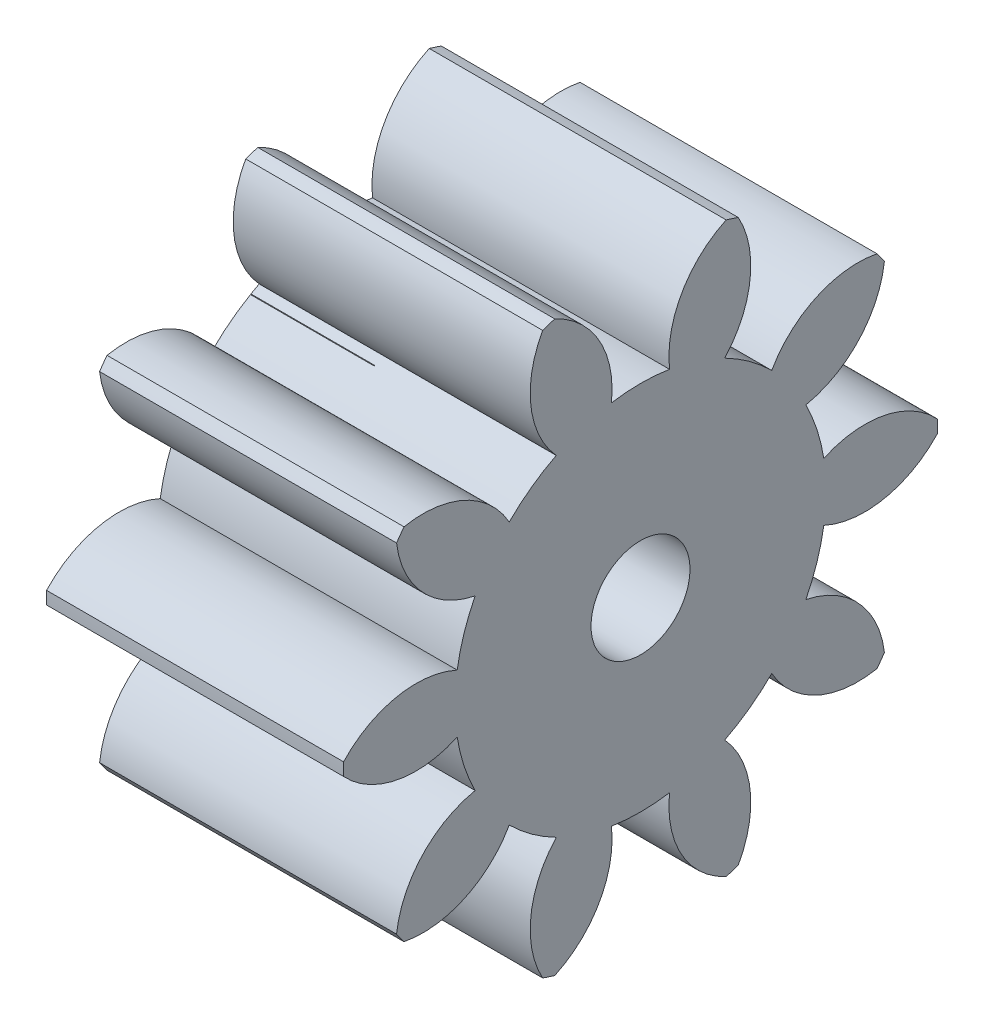
SolidWorks part; units mm, degrees
ref_plane "Plane1" through (0, 0, 0) normal (0, 0, 1) x (1, 0, 0)
ref_plane "Plane2" through (0, 0, 0) normal (0, 1, 0) x (1, 0, 0)
ref_plane "Plane3" through (0, 0, 0) normal (1, 0, 0) x (0, 0, -1)
sketch "HoldingSke" plane through (0, 0, 0) normal (0, 1, 0) x (1, 0, 0)
  line L0 (0, 0) -> (0.4924, -0.0868)
  line L1 (-15, 0) -> (100, 0) construction
  line L2 (0, 0) -> (-2.1039, 2.3779)
  line L3 (0, 0) -> (-11.863, 4.5341)
  line L4 (0, 0) -> (8.5048, 1.4996)
  line L5 (0, 0) -> (-46.8476, -17.4728)
  line L6 (0, 0) -> (-9.9476, -6.7116)
  line L7 (-2.1039, 2.3779) -> (8.6586, 51.2059)
  line L8 (-76.2, 54.61) -> (-75.5, 54.61)
  line L9 (-71.009, 38.7566) -> (-53.1078, 45.2721)
  line L10 (-76.2, 71.12) -> (104.1128, 71.12)
  line L11 (0, 0) -> (-12, 0)
  line L12 (-76.2, 101.6) -> (-76.133, 101.6)
  line L13 (24.9733, 27.94) -> (52.9518, 28.4284)
  line L14 (24.9733, 27.94) -> (24.9743, 27.94)
  line L15 (24.9733, 27.94) -> (100.4006, 29.5858)
  line L16 (-63.627, -2) -> (-12.827, -2)
  circle A0 centre (0, 0) radius 2
  circle A1 centre (0, 0) radius 7.499
  circle A2 centre (0, 0) radius 37.5
  circle A3 centre (0, 0) radius 2
  dimension "MHD" = 14.998
  dimension "Hub_dia" = 75
  dimension "Bore" = 4
  dimension "MBD" = 4
  dimension "Num_teeth" = 10
  dimension "Pitch_radius" = 180.3128
  dimension "Pitch" = 0.5
  dimension "Width" = 12
  dimension "Overall_len" = 50
  dimension "Show_teeth" = 10
  dimension "Thickness" = 12
  dimension "OAL" = 50.0001
  dimension "T_dim" = 0.7
  dimension "Ap" = 20
  dimension "H" = 19.05
  dimension "Backlash" = 0.067
  dimension "Addendum_fac" = 1
  dimension "Dedendum_fac" = 1.25
  dimension "Clearance_fac" = 0.25
  dimension "Dedendum_add" = 0.001
  dimension "Module" = 2
sketch "BasProSke" plane through (0, 0, 0) normal (0, 1, 0) x (1, 0, 0)
  line L0 (-10, 0) -> (60, 0) construction
  line L1 (0, 0) -> (0, 12)
  line L2 (0, 0) -> (12, 0)
  line L3 (12, 0) -> (12, 12)
  line L4 (12, 12) -> (0, 12)
  dimension "Diameter" = 24
  dimension "Thickness" = 12
revolve "Base-Revolve" add sketch "BasProSke" angle 360 about L0
sketch "TooCutSke" plane through (0, 0, 0) normal (1, 0, 0) x (0, 0, -1)
  line L1 (0, 0) -> (0, 107) construction
  line L2 (0, 0) -> (-1.6814, 9.8576) construction
  line L3 (0, 0) -> (-6.1153, 18.8209) construction
  line L4 (-1.6814, 9.8576) -> (-3.0576, 9.4105) construction
  arc A0 (1.1737, 7.4066) -> (-1.1737, 7.4066) centre (0, 0) ccw
  arc A1 (3.4979, 11.5054) -> (-3.4979, 11.5054) centre (0, 0) ccw
  circle A2 centre (0, 0) radius 10 construction
  circle A3 centre (0, 0) radius 9.3969 construction
  arc A4 (-1.1737, 7.4066) -> (-3.4979, 11.5054) centre (-5.1477, 7.8615) ccw
  arc A5 (3.4979, 11.5054) -> (1.1737, 7.4066) centre (5.1477, 7.8615) ccw
  dimension "Root_dia" = 14.998
  dimension "Overcut_dia" = 24.0508
  dimension "Pitch_dia" = 20
  dimension "Base_dia" = 18.7939
  dimension "Flank_rad" = 4
  dimension "Half_ang" = 18
  dimension "Half_CT" = 1.4471
extrude "ToothCut" cut sketch "TooCutSke" along normal through all
fillet "Breaks" [suppressed] radius 0.04
fillet "RootFillets" [suppressed] radius 0.501
pattern_circular "TeethCuts" count 10 every 36 about axis through (-10, 0, 0) along (1, 0, 0) of "ToothCut", "RootFillets", "Breaks"
sketch "HubNeaOneSke" [suppressed] plane through (0, 0, 0) normal (-1, 0, 0) x (0, 0, 1)
  circle A0 centre (0, 0) radius 12.7
  dimension "Diameter" = 14.998
extrude "HubNearOne" [suppressed] add sketch "HubNeaOneSke" along normal blind 38.0001
sketch "HubNeaBotSke" [suppressed] plane through (0, 0, 0) normal (-1, 0, 0) x (0, 0, 1)
  circle A0 centre (0, 0) radius 12.7
  dimension "Diameter" = 14.998
extrude "HubNearBoth" [suppressed] add sketch "HubNeaBotSke" along normal blind 19
ref_plane "FarPln" through (12, 0, 0) normal (1, 0, 0) x (0, 0, -1)
sketch "HubFarSke" [suppressed] plane through (12.7, 0, 0) normal (1, 0, 0) x (0, 0, -1)
  circle A0 centre (0, 0) radius 12.7
  dimension "Diameter" = 14.998
extrude "HubFar" [suppressed] add sketch "HubFarSke" along normal blind 19
sketch "BorSke" plane through (0, 0, 0) normal (1, 0, 0) x (0, 0, -1)
  circle A0 centre (0, 0) radius 2
  dimension "Diameter" = 4
extrude "Bore" cut sketch "BorSke" along normal mid plane 100.0001
sketch "KeySke" [suppressed] plane through (0, 0, 0) normal (1, 0, 0) x (0, 0, -1)
  line L0 (-3.175, 0) -> (-3.175, 12.065)
  line L1 (-3.175, 12.065) -> (3.175, 12.065)
  line L2 (3.175, 12.065) -> (3.175, 0)
  line L3 (0, 0) -> (0, 34) construction
  line L4 (-3.175, 0) -> (3.175, 0)
  dimension "Offset" = 2.7
  dimension "Width" = 1.6
extrude "Keyway" [suppressed] cut sketch "KeySke" along normal mid plane 100.0001
pattern_circular "Keyway2" [suppressed] count 2 every 90 about axis through (-10, 0, 0) along (1, 0, 0)
sketch "Эскиз1" plane through (0, 0, 0) normal (-1, 0, 0) x (0, 0, 1)
  line L1 (7.5056, 0) -> (3.7528, 6.5)
  line L2 (3.7528, 6.5) -> (-3.7528, 6.5)
  line L3 (-3.7528, 6.5) -> (-7.5056, 0)
  line L4 (-7.5056, 0) -> (-3.7528, -6.5)
  line L5 (-3.7528, -6.5) -> (3.7528, -6.5)
  line L6 (3.7528, -6.5) -> (7.5056, 0)
  circle A0 centre (0, 0) radius 6.5 construction
extrude "Вырез-Вытянуть1" cut sketch "Эскиз1" against normal blind 5
equation "' \"Module@HoldingSke\" = 6.35"
equation "' \"Num_teeth@HoldingSke\" = 12"
equation "' \"Ap@HoldingSke\" =  20"
equation "' \"Width@HoldingSke\" = 0.5 * 25.4"
equation "' \"Hub_dia@HoldingSke\"= 1 * 25.4"
equation "' \"Overall_len@HoldingSke\" = 1.0 * 25.4"
equation "' \"Bore@HoldingSke\" = 0.75 * 25.4"
equation "' \"T_dim@HoldingSke\" = 0.1 * 25.4"
equation "' \"Width@KeySke\" = 0.25 * 25.4"
equation "' \"Show_teeth@HoldingSke\" = 13"
equation "' \"Backlash@HoldingSke\" = 0.009 * 25.4"
equation "' \"Addendum_fac@HoldingSke\" = 1.0"
equation "' \"Dedendum_fac@HoldingSke\" = 1.25"
equation "' \"Dedendum_add@HoldingSke\" = 0.00005 * 25.4"
equation "' \"Clearance_fac@HoldingSke\" = 0.25"
equation "\"Pitch@HoldingSke\" = 1 / \"Module@HoldingSke\""
equation "\"Overcut_dia@TooCutSke\" = (\"Num_teeth@HoldingSke\" + 2 * \"Addendum_fac@HoldingSke\") / \"Pitch@HoldingSke\" + 0.002 * 25.4"
equation "\"Pitch_dia@TooCutSke\" = \"Num_teeth@HoldingSke\" / \"Pitch@HoldingSke\""
equation "\"Base_dia@TooCutSke\" = \"Num_teeth@HoldingSke\" / \"Pitch@HoldingSke\" * cos((\"Ap@HoldingSke\"  * 3.14159265 / 180))"
equation "\"Root_dia@TooCutSke\" = (\"Num_teeth@HoldingSke\" + 2) / \"Pitch@HoldingSke\" - 2 * (\"Addendum_fac@HoldingSke\" + \"Dedendum_fac@HoldingSke\") / \"Pitch@HoldingSke\" - \"Dedendum_add@HoldingSke\" * 2"
equation "\"Half_ang@TooCutSke\" = 180 / \"Num_teeth@HoldingSke\""
equation "\"Half_CT@TooCutSke\" = \"Num_teeth@HoldingSke\" / \"Pitch@HoldingSke\" * sin((3.14159265 / 2 / \"Num_teeth@HoldingSke\")) / 2 - 7 * \"Backlash@HoldingSke\" / 4"
equation "\"Flank_rad@TooCutSke\" = \"Num_teeth@HoldingSke\" / \"Pitch@HoldingSke\" / 5"
equation "\"Radius@RootFillets\" = \"Clearance_fac@HoldingSke\" / \"Pitch@HoldingSke\" + \"Dedendum_add@HoldingSke\""
equation "\"Break_rad@Breaks\" = 0.02 / \"Pitch@HoldingSke\""
equation "\"Thickness@HoldingSke\" = \"Width@HoldingSke\""
equation "\"OAL@HoldingSke\" = \"Thickness@HoldingSke\""
equation "\"MHD@HoldingSke\" = (\"Num_teeth@HoldingSke\" + 2) / \"Pitch@HoldingSke\" - 2 * (\"Addendum_fac@HoldingSke\" + \"Dedendum_fac@HoldingSke\")  / \"Pitch@HoldingSke\" - \"Dedendum_add@HoldingSke\" * 2"
equation "\"MBD@HoldingSke\" = (\"Num_teeth@HoldingSke\" + 2) / \"Pitch@HoldingSke\" - 2 * (\"Addendum_fac@HoldingSke\" + \"Dedendum_fac@HoldingSke\")  / \"Pitch@HoldingSke\" - \"Dedendum_add@HoldingSke\" * 2 - 0.002 * 25.4"
equation "\"MHD@HoldingSke\" = ((sgn( \"MHD@HoldingSke\" - \"Hub_dia@HoldingSke\" )-1)*( \"MHD@HoldingSke\" - \"Hub_dia@HoldingSke\" ))/-2+ \"Hub_dia@HoldingSke\""
equation "\"MBD@HoldingSke\" = ((sgn( \"MBD@HoldingSke\" - \"Bore@HoldingSke\" )-1)*( \"MBD@HoldingSke\" - \"Bore@HoldingSke\" ))/-2+ \"Bore@HoldingSke\""
equation "\"OAL@HoldingSke\" = ((sgn( \"OAL@HoldingSke\" - \"Overall_len@HoldingSke\" )+1)*( \"OAL@HoldingSke\" - \"Overall_len@HoldingSke\" ))/2 + \"Overall_len@HoldingSke\" + 0.000002 * 25.4"
equation "\"Num_teeth@TeethCuts\" = int( \"Show_teeth@HoldingSke\" ) + 1"
equation "\"Num_teeth@TeethCuts\" = ((sgn( \"Num_teeth@TeethCuts\" - \"Num_teeth@HoldingSke\" )-1)*( \"Num_teeth@TeethCuts\" - \"Num_teeth@HoldingSke\" ))/-2+ \"Num_teeth@HoldingSke\""
equation "\"Num_teeth@TeethCuts\" = ((sgn( \"Num_teeth@TeethCuts\" - 2.0)+1)*( \"Num_teeth@TeethCuts\" - 2.0))/2 +2.0"
equation "\"Angle@TeethCuts\" = 360.0 / \"Num_teeth@HoldingSke\""
equation "\"Diameter@BasProSke\" = (\"Num_teeth@HoldingSke\" + 2 * \"Addendum_fac@HoldingSke\") / \"Pitch@HoldingSke\""
equation "\"Thickness@BasProSke\"  = \"Thickness@HoldingSke\""
equation "' \"Fillet_rad@BasProSke\" =  \"Thickness@HoldingSke\" * 0.05"
equation "\"MHD@HoldingSke\" = ((sgn( \"MHD@HoldingSke\" - \"Root_dia@TooCutSke\" )-1)*( \"MHD@HoldingSke\" - \"Root_dia@TooCutSke\" ))/-2+ \"Root_dia@TooCutSke\""
equation "\"Diameter@HubNeaOneSke\" = \"MHD@HoldingSke\""
equation "\"Length@HubNearOne\" = \"OAL@HoldingSke\" - \"Thickness@BasProSke\""
equation "\"Diameter@HubNeaBotSke\" = \"MHD@HoldingSke\""
equation "\"Length@HubNearBoth\" = ( \"OAL@HoldingSke\" - \"Thickness@BasProSke\" ) / 2.0"
equation "\"Thickness@FarPln\" = \"Thickness@BasProSke\""
equation "\"Diameter@HubFarSke\" = \"MHD@HoldingSke\""
equation "\"Length@HubFar\" = ( \"OAL@HoldingSke\" - \"Thickness@BasProSke\" ) / 2.0"
equation "\"Diameter@BorSke\" = \"MBD@HoldingSke\""
equation "\"D1@Bore\" = \"OAL@HoldingSke\" * 2.0"
equation "\"D1@Keyway\" = \"OAL@HoldingSke\" * 2.0"
equation "\"Offset@KeySke\" = \"T_dim@HoldingSke\" + \"MBD@HoldingSke\" / 2.0"
